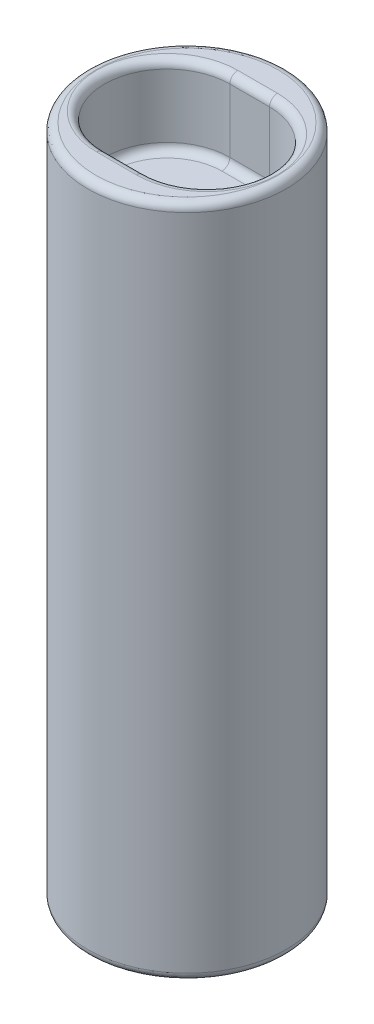
SolidWorks part; units mm, degrees
ref_plane "Front Plane" through (0, 0, 0) normal (0, 0, 1) x (1, 0, 0)
ref_plane "Top Plane" through (0, 0, 0) normal (0, 1, 0) x (1, 0, 0)
ref_plane "Right Plane" through (0, 0, 0) normal (1, 0, 0) x (0, 0, -1)
sketch "Sketch1" plane through (0, 0, 0) normal (0, 1, 0) x (1, 0, 0)
  line L0 (-1.27, 0) -> (1.27, 0) construction
  line L1 (-1.27, 3.937) -> (1.27, 3.937)
  line L2 (-1.27, -3.937) -> (1.27, -3.937)
  line L3 (-1.27, 4.0132) -> (1.27, 4.0132)
  line L4 (-1.27, -4.0132) -> (1.27, -4.0132)
  arc A0 (-1.27, 3.937) -> (-1.27, -3.937) centre (-1.27, 0) ccw
  arc A1 (1.27, -3.937) -> (1.27, 3.937) centre (1.27, 0) ccw
  arc A2 (1.27, -4.0132) -> (1.27, 4.0132) centre (1.27, 0) ccw
  arc A3 (-1.27, 4.0132) -> (-1.27, -4.0132) centre (-1.27, 0) ccw
  circle A4 centre (0, 0) radius 6.35
  dimension "D1" = 2.54
  dimension "D2" = 7.874
  dimension "D4" = 12.7
  dimension "D3" = 0.0762
extrude "Boss-Extrude1" add sketch "Sketch1" along normal blind 5.08 contours A4 A3 L3 A2 L4
sketch "Sketch2" plane through (0, 0, 0) normal (0, -1, 0) x (1, 0, 0)
  circle A1 centre (0, 0) radius 6.35
  circle A2 centre (0, 0) radius 6.35
  dimension "D1" = 0
extrude "Boss-Extrude2" add sketch "Sketch2" along normal blind 38.1
fillet "Fillet1" radius 0.508 10 edges at (0, 0, 4.0132) (-5.2832, 0, 0) (0, 0, -4.0132) (0, 5.08, 4.0132) (-5.2832, 5.08, 0) (0, 5.08, -4.0132) (5.2832, 0, 0) (5.2832, 5.08, 0) (0, 5.08, 6.35) (0, -38.1, -6.35)
